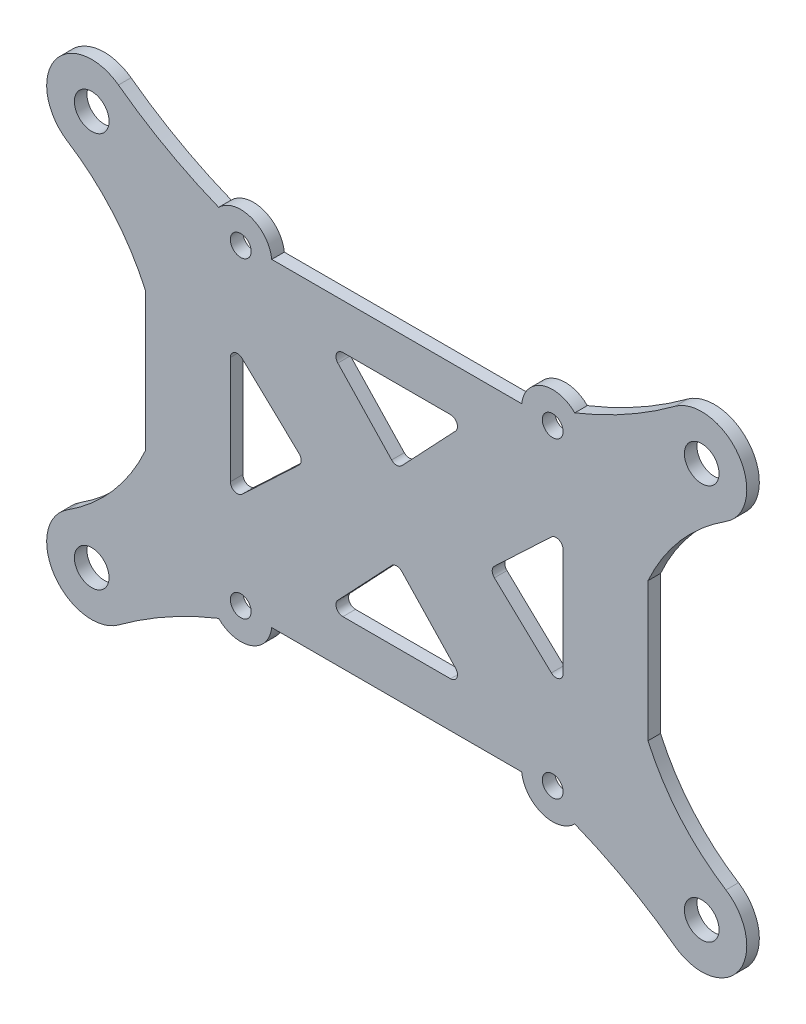
SolidWorks part; units mm, degrees
ref_plane "Front Plane" through (0, 0, 0) normal (0, 0, 1) x (1, 0, 0)
ref_plane "Top Plane" through (0, 0, 0) normal (0, 1, 0) x (1, 0, 0)
ref_plane "Right Plane" through (0, 0, 0) normal (1, 0, 0) x (0, 0, -1)
sketch "Sketch1" plane through (0, 0, 0) normal (0, 0, 1) x (1, 0, 0)
  line L0 (-36.25, 0) -> (36.25, 0) construction
  line L1 (36.25, -10) -> (36.25, 10)
  line L2 (-36.25, -10) -> (-36.25, 10)
  line L3 (0, -23) -> (0, 23) construction
  line L4 (-18.0279, 23) -> (18.0279, 23)
  line L5 (-18.0279, -23) -> (18.0279, -23)
  circle A0 centre (-44, -28.5) radius 2.5
  arc A1 (-18.0279, 23) -> (-25.684, 25.68) centre (-22.5, 22.5) ccw
  arc A2 (-18.0279, -23) -> (-25.684, -25.68) centre (-22.5, -22.5) cw
  circle A3 centre (-44, 28.5) radius 2.5
  arc A5 (18.0279, 23) -> (25.684, 25.68) centre (22.5, 22.5) cw
  circle A6 centre (44, -28.5) radius 2.5
  circle A7 centre (44, 28.5) radius 2.5
  arc A9 (40.1406, -33.7302) -> (47.4945, -23.0193) centre (44, -28.5) ccw
  arc A10 (36.25, -10) -> (47.4945, -23.0193) centre (63.6232, 2.2763) ccw
  arc A11 (36.25, 10) -> (47.4945, 23.0193) centre (63.6232, -2.2763) cw
  arc A12 (-36.25, 10) -> (-47.4945, 23.0193) centre (-63.6232, -2.2763) ccw
  arc A13 (-36.25, -10) -> (-47.4945, -23.0193) centre (-63.6232, 2.2763) cw
  arc A14 (-40.1406, -33.7302) -> (-47.4945, -23.0193) centre (-44, -28.5) cw
  arc A15 (40.1406, 33.7302) -> (47.4945, 23.0193) centre (44, 28.5) cw
  arc A16 (-40.1406, 33.7302) -> (-47.4945, 23.0193) centre (-44, 28.5) ccw
  arc A17 (18.0279, -23) -> (25.684, -25.68) centre (22.5, -22.5) ccw
  arc A18 (-40.1406, 33.7302) -> (-25.684, 25.68) centre (-1.5465, 86.0321) ccw
  arc A19 (-40.1406, -33.7302) -> (-25.684, -25.68) centre (-1.5465, -86.0321) cw
  arc A20 (40.1406, -33.7302) -> (25.684, -25.68) centre (1.5465, -86.0321) ccw
  arc A21 (40.1406, 33.7302) -> (25.684, 25.68) centre (1.5465, 86.0321) cw
  point P4 (0, 0)
  point P8 (36.25, 0)
  point P11 (-36.25, 0)
  point P21 (0, 0)
  dimension "D4" = 5
  dimension "D8" = 9
  dimension "D9" = 21.5
  dimension "D12" = 130
  dimension "D13" = 13
  dimension "D14" = 60
  dimension "D15" = 65
  dimension "D1" = 72.5
  dimension "D2" = 20
  dimension "D3" = 18.5
  dimension "D5" = 7.75
  dimension "D6" = 13.75
  dimension "D7" = 12.5
  dimension "D10" = 0.5
  dimension "D16" = 3.18
  dimension "D17" = 3.184
extrude "Boss-Extrude1" add sketch "Sketch1" along normal blind 1.8139
sketch "Sketch2" plane through (0, 0, 1.8139) normal (0, 0, 1) x (1, 0, 0)
  line L0 (0, 0) -> (-20.6183, 0) construction
  line L1 (0, 0) -> (0, 5.8271) construction
  line L2 (-7.765, 16.5) -> (7.765, 16.5)
  line L3 (18.0279, 23) -> (-18.0279, 23) construction
  line L4 (-8.4918, 14.8132) -> (-0.7268, 6.5962)
  line L5 (8.4918, 14.8132) -> (0.7268, 6.5962)
  line L6 (-7.765, -16.5) -> (7.765, -16.5)
  line L7 (-8.4918, -14.8132) -> (-0.7268, -6.5962)
  line L8 (8.4918, -14.8132) -> (0.7268, -6.5962)
  line L9 (-24, -7.765) -> (-24, 7.765)
  line L10 (-36.25, 10) -> (-36.25, -10) construction
  line L11 (-22.3135, 8.4921) -> (-14.09, 0.7271)
  line L12 (-22.3135, -8.4921) -> (-14.09, -0.7271)
  line L13 (24, -7.765) -> (24, 7.765)
  line L14 (22.3135, 8.4921) -> (14.09, 0.7271)
  line L15 (22.3135, -8.4921) -> (14.09, -0.7271)
  circle A0 centre (-22.5, 22.5) radius 1.5
  circle A1 centre (-22.5, -22.5) radius 1.5
  circle A2 centre (22.5, -22.5) radius 1.5
  circle A3 centre (22.5, 22.5) radius 1.5
  arc A4 (7.765, 16.5) -> (8.4918, 14.8132) centre (7.765, 15.5) cw
  arc A5 (-0.7268, 6.5962) -> (0.7268, 6.5962) centre (0, 7.2831) ccw
  arc A6 (-7.765, 16.5) -> (-8.4918, 14.8132) centre (-7.765, 15.5) ccw
  arc A7 (-7.765, -16.5) -> (-8.4918, -14.8132) centre (-7.765, -15.5) cw
  arc A8 (7.765, -16.5) -> (8.4918, -14.8132) centre (7.765, -15.5) ccw
  arc A9 (-0.7268, -6.5962) -> (0.7268, -6.5962) centre (0, -7.2831) cw
  arc A10 (-24, -7.765) -> (-22.3135, -8.4921) centre (-23, -7.765) ccw
  arc A11 (-14.09, 0.7271) -> (-14.09, -0.7271) centre (-14.7766, 0) cw
  arc A12 (-24, 7.765) -> (-22.3135, 8.4921) centre (-23, 7.765) cw
  arc A13 (24, 7.765) -> (22.3135, 8.4921) centre (23, 7.765) ccw
  arc A14 (24, -7.765) -> (22.3135, -8.4921) centre (23, -7.765) cw
  arc A15 (14.09, 0.7271) -> (14.09, -0.7271) centre (14.7766, 0) ccw
  point P16 (0, 16.5)
  point P20 (10.0859, 16.5)
  point P26 (-10.0859, 16.5)
  point P39 (-24, 0)
  point P44 (-24, -10.0846)
  point P47 (-13.32, 0)
  point P50 (-24, 10.0846)
  dimension "D1" = 3
  dimension "D4" = 1
  dimension "D7" = 1
  dimension "D2" = 6.5
  dimension "D3" = 15.53
  dimension "D5" = 12.25
  dimension "D6" = 10.68
  dimension "D8" = 1.5
  dimension "D9" = 15.53
extrude "Cut-Extrude1" cut sketch "Sketch2" against normal through all
